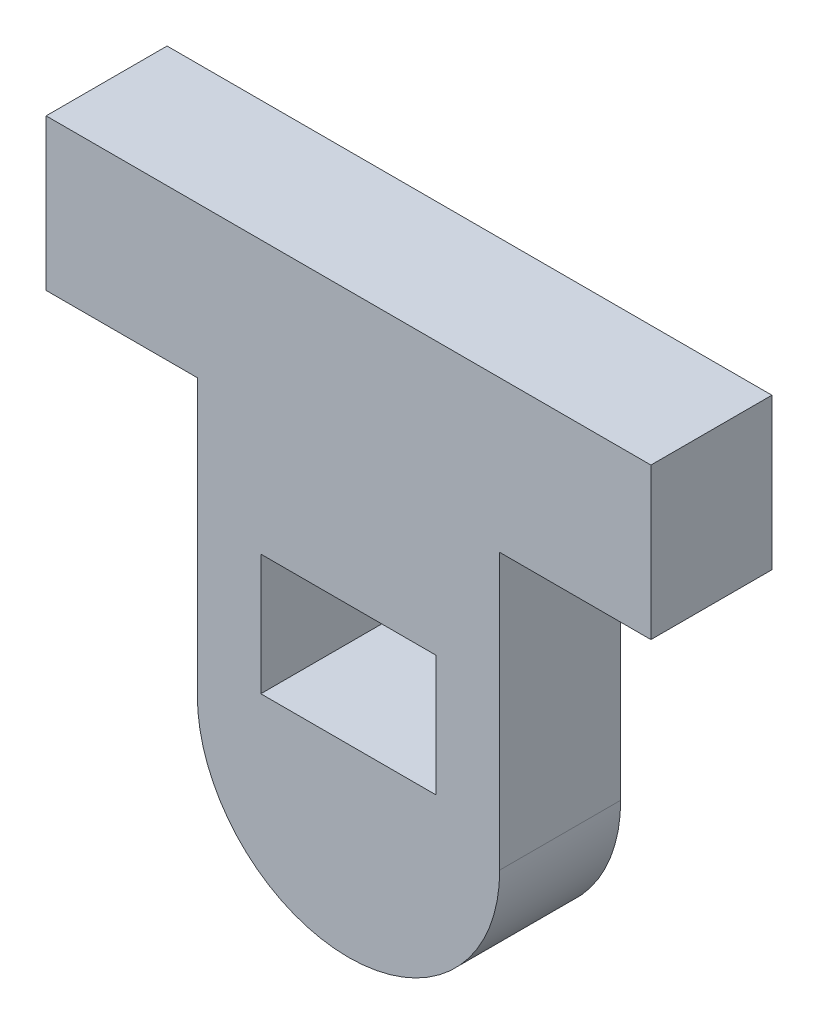
SolidWorks part; units mm, degrees
ref_plane "Front Plane" through (0, 0, 0) normal (0, 0, 1) x (1, 0, 0)
ref_plane "Top Plane" through (0, 0, 0) normal (0, 1, 0) x (1, 0, 0)
ref_plane "Right Plane" through (0, 0, 0) normal (1, 0, 0) x (0, 0, -1)
sketch "Sketch1" plane through (0, 0, 0) normal (0, 0, 1) x (1, 0, 0)
  line L0 (12.7, 18.542) -> (19.05, 18.542)
  line L2 (0, 6.985) -> (0, 18.542)
  line L4 (12.7, 6.985) -> (12.7, 18.542)
  line L5 (19.05, 18.542) -> (19.05, 24.892)
  line L6 (19.05, 24.892) -> (-6.35, 24.892)
  line L7 (-6.35, 24.892) -> (-6.35, 18.542)
  line L8 (-6.35, 18.542) -> (0, 18.542)
  line L9 (0, 18.542) -> (12.7, 18.542) construction
  line L10 (6.35, 18.542) -> (6.35, 0.635) construction
  arc A0 (0, 6.985) -> (12.7, 6.985) centre (6.35, 6.985) ccw
  dimension "D1" = 12.7
  dimension "D3" = 6.35
  dimension "D4" = 6.35
  dimension "D2" = 17.907
extrude "Boss-Extrude1" add sketch "Sketch1" along normal blind 5.08
sketch "Sketch2" plane through (0, 0, 5.08) normal (0, 0, 1) x (1, 0, 0)
  line L0 (0, 18.542) -> (12.7, 18.542) construction
  line L1 (6.35, 18.542) -> (6.35, 13.462) construction
  line L2 (6.35, 13.462) -> (10.033, 13.462)
  line L3 (10.033, 13.462) -> (10.033, 8.382)
  line L4 (10.033, 8.382) -> (2.667, 8.382)
  line L5 (2.667, 8.382) -> (2.667, 13.462)
  line L6 (2.667, 13.462) -> (6.35, 13.462)
  dimension "D1" = 5.08
  dimension "D2" = 5.08
  dimension "D3" = 3.683
extrude "Cut-Extrude1" cut sketch "Sketch2" against normal through all
equation "\"FoamCore\" = \".2\""
equation "\"MDF\" = \".2\""
equation "\"GMaterial\"= \".2\""
equation "\"PVCMountDiameter\" = \"0.5in\""
equation "\"PVCMountDistanceToEdge\" = \"0.5\""
equation "\"PVCThickness\" = \"0.13in\""
equation "\"PVCDiameter\" = 1.5in"
equation "\"BaseWidth\" = \"8in\""
equation "\"BaseLength\" = \"10in\""
equation "\"BallDiameter\" = \"38mm\""
equation "\"BaseGap\" = \"4in\""
equation "\"FunnelTopDiameter\" = \"8in\""
equation "\"FunnelTopDepth\" = \"0.5in\""
equation "\"BallGap\" = \"0.1in\""
equation "\"FunnelLength\" = 3in"
equation "\"FunnelMaterial\" = 0.1in"
equation "\"FunnelLowerDiameter\" = 1.9in"
equation "\"FunnelDepth\" = 1.5in"
equation "\"FunnelBendLength\" = 2*pi*\"FunnelLowerDiameter\"/2*135"
equation "\"AmmoFeederLength\" = 1.5in + 76mm"
equation "\"WheelThickness\" = 0.5in"
equation "\"LauncherWheelDiameter\" = 76mm"
equation "\"MotorFrontLength\" = 0.95in"
equation "\"MotorBodyTotalLength\" = 2.03in"
equation "\"MotorFrontDiameter\" = 1.5in"
equation "\"MotorLowerDriveshaftDiameter\" = 0.46in"
equation "\"MotorLowerDriveshaftThickness\" = 0.25in"
equation "\"MotorFullDriveshaftLength\" = 0.78in"
equation "\"MotorDriveshaftDiameter\" = 0.23in"
equation "\"MotorDriveshaftFlatThickness\" = 0.2in"
equation "\"MotorRearDiameter\" = 31.9mm"
equation "\"MotorDriveshaftBottomToTop\" = 31.1mm"
equation "\"MotorFlatDriveshaftLength\" = 11.7mm"
equation "\"MotorDistanceBetweenLowerandTopHoles\" = 0.5in"
equation "\"MotorMountsDistanceFromEdge\" = 0.06in"
equation "\"MotorScrewMountDiameter\" = 0.1in"
equation "\"MotorScrewMountDepth\" = 0.13in"
equation "\"HBRidgeScrewHoleDeep\" = 0.18in"
equation "\"MotorMountWidth\" = \"1.61in\""
equation "\"MotorMountLength\" = \"1.58in\""
equation "\"MotorMountToEdgeGap\" = \"3.3mm\""
equation "\"MotorMountToInsideEdgeGap\" = \"6.5mm\""
equation "\"MotorMountToMountWidthGap\" = \"25.8mm\""
equation "\"MotorMountToMountLengthGap\" = \"20.5mm\""
equation "\"MotorMountMaterialThickness\" = 1.6mm"
equation "\"MotorMountBaseScrewholeDiameter\" = 3.8mm"
equation "\"MotorMountBaseDistancebetweenHoles\" = 0.8in"
equation "\"MotorMountHeight\" = 1.85in"
equation "\"HBridgeWidth\" = 2.25in"
equation "\"HBridgeLength\" = 1.40in"
equation "\"UnoWidth\" = 3.13in"
equation "\"UnoLength\" = 3.06in"
equation "\"BatteryWidth\" = 1.15in"
equation "\"BatteryLength\" = 3.86in"
equation "\"ScrewDiameter\" = 2.7mm"
equation "\"MotorMountFaceScrewtoBase\" = 0.46in"
equation "\"MotorMountFaceDistanceBetweenScrews\" = 0.95in"
equation "\"MotorMountFaceMiddletoEdge\" = 0.16in"
equation "\"MotorMountFaceBottomtoEdge\" = 0.42in"
equation "\"MotorMountCenterholeHeight\" = 1.04in"
equation "\"MotorMountCenterholetoEdge\" = 0.25in"
equation "\"MovingWheelDiameter\" = 76mm"
equation "\"MovingWheelThickness\" = 0.5in"
equation "\"BraceLength\" = 1in"
equation "\"BraceVerticalOffset\" = 3.5in"
equation "\"BraceHorizontalOffset\" = 2.5in"
equation "\"BaseToBaseDistance\" = 3in"
equation "\"PVCOutsideDiameter\" = \"PVCDiameter\" + 2*\"PVCThickness\""
equation "\"Distancebetweenwalls\" = 6in"
equation "\"Slidewidth\" = 0.3in"
equation "\"Slidelength\" = 0.8in"
equation "\"D1@Sketch1\"=\"BraceLength\"/2"
equation "\"AmmoFeederCutoffLength\"= \"MovingWheelDiameter\""
equation "\"Bottomtofloor\" = 0.53in"
equation "\"D3@Sketch1\"=\"BraceLength\"/4"
equation "\"D4@Sketch1\"=\"BraceLength\"/4"
equation "\"D1@Boss-Extrude1\"=\"MDF\""
equation "\"D1@Sketch2\"=\"MDF\""
equation "\"D2@Sketch2\"=\"MDF\""
equation "\"D3@Sketch2\"=\"Slidewidth\"/2-0.005"
